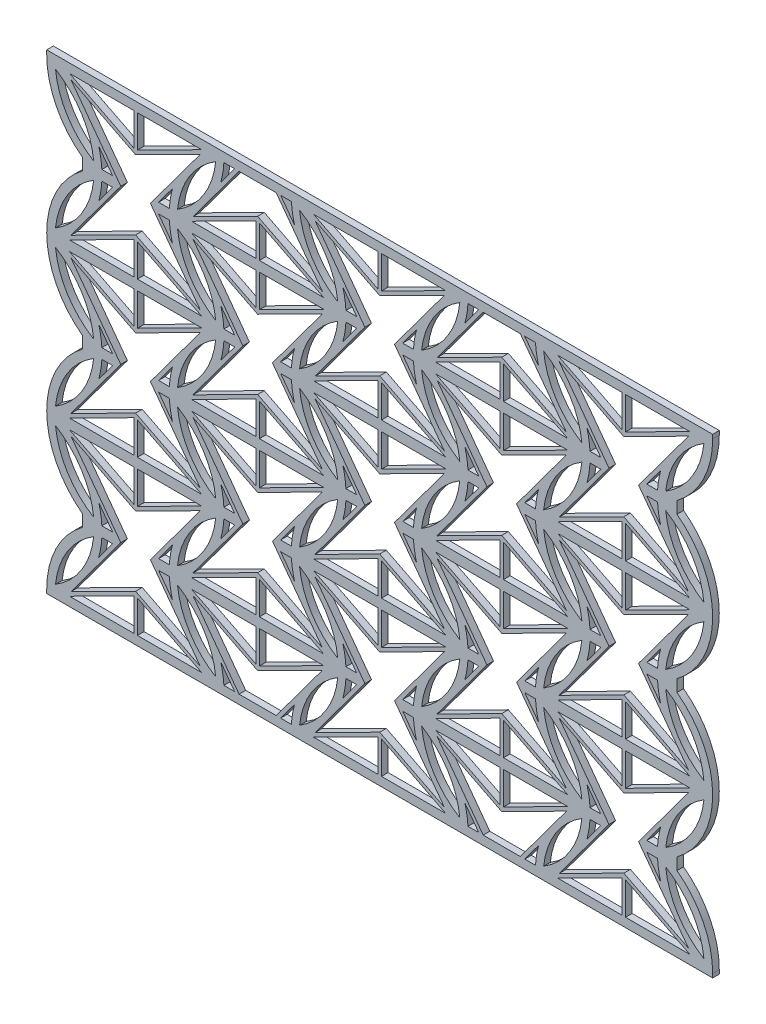
SolidWorks part; units mm, degrees
ref_plane "Front Plane" through (0, 0, 0) normal (0, 0, 1) x (1, 0, 0)
ref_plane "Top Plane" through (0, 0, 0) normal (0, 1, 0) x (1, 0, 0)
ref_plane "Right Plane" through (0, 0, 0) normal (1, 0, 0) x (0, 0, -1)
sketch "Sketch1" plane through (0, 0, 0) normal (0, 0, 1) x (1, 0, 0)
  line L1 (3.3776, -1.5756) -> (5.3265, -1.5756)
  line L3 (-16.8885, 13.319) -> (-16.8885, 14.0355) construction
  line L6 (15.3115, 14.0355) -> (15.3115, 13.319) construction
  line L8 (-4.9547, -1.5756) -> (-6.9036, -1.5756)
  line L9 (-16.8885, -14.6332) -> (-16.8885, -15.3497)
  line L10 (-4.9547, 0.2614) -> (-7.4694, 3.6583)
  line L11 (-16.8885, -15.3497) -> (15.3115, -15.3497)
  line L13 (-10.427, 0.423) -> (-10.427, -1.7372)
  line L16 (-16.8885, 13.319) -> (15.3115, 13.319) construction
  line L17 (11.1755, 12.4005) -> (-0.4651, 12.4005)
  line L21 (3.3776, 0.2614) -> (5.8924, 3.6583)
  line L23 (-1.112, 6.5213) -> (-12.7526, 12.4005)
  line L24 (3.3776, -1.5756) -> (5.8924, -4.9725)
  line L25 (3.3776, 0.2614) -> (5.3265, 0.2614)
  line L27 (-4.9547, -1.5756) -> (-7.4694, -4.9725)
  line L28 (-4.9547, 0.2614) -> (-6.9036, 0.2614)
  line L30 (-16.8885, 14.0355) -> (15.3115, 14.0355) construction
  line L31 (-1.112, 12.4005) -> (-12.7526, 12.4005)
  line L33 (15.3115, -15.3497) -> (15.3115, -14.6332) construction
  line L34 (-16.8885, -14.6332) -> (15.3115, -14.6332) construction
  line L36 (8.85, 0.423) -> (8.85, -1.7372) construction
  line L40 (-0.4651, 6.5213) -> (11.1755, 12.4005)
  line L41 (-0.7885, 4.2888) -> (-0.7885, -49995.7112) construction
  line L42 (-1.9767, -0.6571) -> (49998.0233, -0.6571) construction
  line L43 (-1.112, 12.4005) -> (-1.112, 6.5213)
  line L44 (-0.4651, 12.4005) -> (-0.4651, 6.5213)
  line L45 (-0.7885, -6.9474) -> (10.932, -12.867)
  line L46 (10.932, -12.867) -> (1.8927, -0.6571)
  line L47 (10.932, 11.5528) -> (1.8927, -0.6571)
  line L48 (-0.7885, 5.6332) -> (10.932, 11.5528)
  line L49 (-0.7885, 5.6332) -> (-12.509, 11.5528)
  line L50 (-12.509, 11.5528) -> (-3.4698, -0.6571)
  line L51 (-12.509, -12.867) -> (-3.4698, -0.6571)
  line L52 (-0.7885, -6.9474) -> (-12.509, -12.867)
  line L53 (-0.4651, -7.8355) -> (11.1755, -13.7147)
  line L54 (-0.4651, -13.7147) -> (-0.4651, -7.8355)
  line L55 (11.1755, -13.7147) -> (-0.4651, -13.7147)
  line L56 (-1.112, -13.7147) -> (-1.112, -7.8355)
  line L57 (-1.112, -7.8355) -> (-12.7526, -13.7147)
  line L58 (-1.112, -13.7147) -> (-12.7526, -13.7147)
  line L59 (25.4851, 14.2376) -> (27.434, 14.2376)
  line L60 (33.283, 0.2614) -> (21.6424, 0.2614)
  line L61 (37.4189, -1.3736) -> (37.4189, -0.6571) construction
  line L62 (21.3189, 19.6093) -> (9.5984, 25.5289)
  line L63 (5.2189, 27.2952) -> (37.4189, 27.2952) construction
  line L64 (9.5984, 1.1091) -> (18.6377, 13.319)
  line L65 (17.1528, 14.2376) -> (15.2039, 14.2376)
  line L66 (21.6424, 6.1407) -> (33.283, 0.2614)
  line L67 (20.9955, 0.2614) -> (9.3549, 0.2614)
  line L68 (17.1528, 12.4005) -> (15.2039, 12.4005)
  line L69 (17.1528, 14.2376) -> (14.638, 17.6344)
  line L70 (25.4851, 14.2376) -> (27.9998, 17.6344)
  line L71 (9.5984, 25.5289) -> (18.6377, 13.319)
  line L72 (11.6804, 14.3991) -> (11.6804, 12.239) construction
  line L73 (20.9955, 6.1407) -> (9.3549, 0.2614)
  line L74 (5.2189, 28.0116) -> (37.4189, 28.0116) construction
  line L75 (33.0394, 1.1091) -> (24.0002, 13.319)
  line L76 (25.4851, 12.4005) -> (27.434, 12.4005)
  line L77 (21.3189, 7.0287) -> (9.5984, 1.1091)
  line L78 (5.2189, 27.2952) -> (5.2189, 28.0116) construction
  line L79 (33.283, 26.3766) -> (21.6424, 26.3766)
  line L80 (21.6424, 20.4974) -> (33.283, 26.3766)
  line L81 (30.9574, 14.3991) -> (30.9574, 12.239) construction
  line L82 (20.9955, 20.4974) -> (9.3549, 26.3766)
  line L83 (20.9955, 26.3766) -> (20.9955, 20.4974)
  line L84 (21.3189, 7.0287) -> (33.0394, 1.1091)
  line L85 (25.4851, 12.4005) -> (27.9998, 9.0036)
  line L86 (33.0394, 25.5289) -> (24.0002, 13.319)
  line L87 (5.2189, -0.6571) -> (5.2189, -1.3736) construction
  line L88 (17.1528, 12.4005) -> (14.638, 9.0036)
  line L89 (20.9955, 0.2614) -> (20.9955, 6.1407)
  line L90 (5.2189, -1.3736) -> (37.4189, -1.3736) construction
  line L91 (20.9955, 26.3766) -> (9.3549, 26.3766)
  line L92 (21.6424, 0.2614) -> (21.6424, 6.1407)
  line L93 (37.4189, 28.0116) -> (37.4189, 27.2952) construction
  line L94 (21.3189, 19.6093) -> (33.0394, 25.5289)
  line L95 (5.2189, -0.6571) -> (37.4189, -0.6571) construction
  line L96 (21.6424, 26.3766) -> (21.6424, 20.4974)
  line L97 (47.5925, 28.2137) -> (49.5414, 28.2137)
  line L98 (55.3904, 14.2376) -> (43.7498, 14.2376)
  line L99 (59.5264, 12.6026) -> (59.5264, 13.319) construction
  line L100 (43.4264, 33.5855) -> (31.7059, 39.5051)
  line L101 (27.3264, 41.2713) -> (59.5264, 41.2713) construction
  line L102 (31.7059, 15.0853) -> (40.7451, 27.2952)
  line L103 (39.2602, 28.2137) -> (37.3113, 28.2137)
  line L104 (43.7498, 20.1168) -> (55.3904, 14.2376)
  line L105 (43.1029, 14.2376) -> (31.4623, 14.2376)
  line L106 (39.2602, 26.3766) -> (37.3113, 26.3766)
  line L107 (39.2602, 28.2137) -> (36.7455, 31.6106)
  line L108 (47.5925, 28.2137) -> (50.1073, 31.6106)
  line L109 (31.7059, 39.5051) -> (40.7451, 27.2952)
  line L110 (33.7879, 28.3752) -> (33.7879, 26.2151) construction
  line L111 (43.1029, 20.1168) -> (31.4623, 14.2376)
  line L112 (27.3264, 41.9878) -> (59.5264, 41.9878) construction
  line L113 (55.1469, 15.0853) -> (46.1076, 27.2952)
  line L114 (47.5925, 26.3766) -> (49.5414, 26.3766)
  line L115 (43.4264, 21.0049) -> (31.7059, 15.0853)
  line L116 (27.3264, 41.2713) -> (27.3264, 41.9878) construction
  line L117 (55.3904, 40.3528) -> (43.7498, 40.3528)
  line L118 (43.7498, 34.4735) -> (55.3904, 40.3528)
  line L119 (53.0649, 28.3752) -> (53.0649, 26.2151) construction
  line L120 (43.1029, 34.4735) -> (31.4623, 40.3528)
  line L121 (43.1029, 40.3528) -> (43.1029, 34.4735)
  line L122 (43.4264, 21.0049) -> (55.1469, 15.0853)
  line L123 (47.5925, 26.3766) -> (50.1073, 22.9798)
  line L124 (55.1469, 39.5051) -> (46.1076, 27.2952)
  line L125 (27.3264, 13.319) -> (27.3264, 12.6026) construction
  line L126 (39.2602, 26.3766) -> (36.7455, 22.9798)
  line L127 (43.1029, 14.2376) -> (43.1029, 20.1168)
  line L128 (27.3264, 12.6026) -> (59.5264, 12.6026) construction
  line L129 (43.1029, 40.3528) -> (31.4623, 40.3528)
  line L130 (43.7498, 14.2376) -> (43.7498, 20.1168)
  line L131 (59.5264, 41.9878) -> (59.5264, 41.2713) construction
  line L132 (43.4264, 33.5855) -> (55.1469, 39.5051)
  line L133 (27.3264, 13.319) -> (59.5264, 13.319) construction
  line L134 (43.7498, 40.3528) -> (43.7498, 34.4735)
  line L135 (69.7, 42.1898) -> (71.6489, 42.1898)
  line L136 (77.4979, 28.2137) -> (65.8573, 28.2137)
  line L137 (81.6338, 26.5787) -> (81.6338, 27.2952) construction
  line L138 (65.5338, 47.5616) -> (53.8133, 53.4812)
  line L139 (49.4338, 55.2475) -> (81.6338, 55.2475) construction
  line L140 (53.8133, 29.0614) -> (62.8526, 41.2713)
  line L141 (61.3677, 42.1898) -> (59.4188, 42.1898)
  line L142 (65.8573, 34.093) -> (77.4979, 28.2137)
  line L143 (65.2104, 28.2137) -> (53.5698, 28.2137)
  line L144 (61.3677, 40.3528) -> (59.4188, 40.3528)
  line L145 (61.3677, 42.1898) -> (58.8529, 45.5867)
  line L146 (69.7, 42.1898) -> (72.2147, 45.5867)
  line L147 (53.8133, 53.4812) -> (62.8526, 41.2713)
  line L148 (55.8953, 42.3514) -> (55.8953, 40.1913) construction
  line L149 (65.2104, 34.093) -> (53.5698, 28.2137)
  line L150 (49.4338, 55.9639) -> (81.6338, 55.9639) construction
  line L151 (77.2543, 29.0614) -> (68.2151, 41.2713)
  line L152 (69.7, 40.3528) -> (71.6489, 40.3528)
  line L153 (65.5338, 34.981) -> (53.8133, 29.0614)
  line L154 (49.4338, 55.2475) -> (49.4338, 55.9639) construction
  line L155 (77.4979, 54.3289) -> (65.8573, 54.3289)
  line L156 (65.8573, 48.4497) -> (77.4979, 54.3289)
  line L157 (75.1723, 42.3514) -> (75.1723, 40.1913) construction
  line L158 (65.2104, 48.4497) -> (53.5698, 54.3289)
  line L159 (65.2104, 54.3289) -> (65.2104, 48.4497)
  line L160 (65.5338, 34.981) -> (77.2543, 29.0614)
  line L161 (69.7, 40.3528) -> (72.2147, 36.9559)
  line L162 (77.2543, 53.4812) -> (68.2151, 41.2713)
  line L163 (49.4338, 27.2952) -> (49.4338, 26.5787) construction
  line L164 (61.3677, 40.3528) -> (58.8529, 36.9559)
  line L165 (65.2104, 28.2137) -> (65.2104, 34.093)
  line L166 (49.4338, 26.5787) -> (81.6338, 26.5787) construction
  line L167 (65.2104, 54.3289) -> (53.5698, 54.3289)
  line L168 (65.8573, 28.2137) -> (65.8573, 34.093)
  line L169 (81.6338, 55.9639) -> (81.6338, 55.2475) construction
  line L170 (65.5338, 47.5616) -> (77.2543, 53.4812)
  line L171 (49.4338, 27.2952) -> (81.6338, 27.2952) construction
  line L172 (65.8573, 54.3289) -> (65.8573, 48.4497)
  line L173 (91.8074, 56.166) -> (93.7563, 56.166)
  line L174 (99.6053, 42.1898) -> (87.9647, 42.1898)
  line L175 (103.7413, 40.5549) -> (103.7413, 41.2713) construction
  line L176 (87.6413, 61.5378) -> (75.9208, 67.4574)
  line L177 (71.5413, 69.2236) -> (103.7413, 69.2236) construction
  line L178 (75.9208, 43.0376) -> (84.96, 55.2475)
  line L179 (83.4751, 56.166) -> (81.5262, 56.166)
  line L180 (87.9647, 48.0691) -> (99.6053, 42.1898)
  line L181 (87.3178, 42.1898) -> (75.6772, 42.1898)
  line L182 (83.4751, 54.3289) -> (81.5262, 54.3289)
  line L183 (83.4751, 56.166) -> (80.9604, 59.5629)
  line L184 (91.8074, 56.166) -> (94.3222, 59.5629)
  line L185 (75.9208, 67.4574) -> (84.96, 55.2475)
  line L186 (78.0027, 56.3275) -> (78.0027, 54.1674) construction
  line L187 (87.3178, 48.0691) -> (75.6772, 42.1898)
  line L188 (71.5413, 69.94) -> (103.7413, 69.94)
  line L189 (99.3618, 43.0376) -> (90.3225, 55.2475)
  line L190 (91.8074, 54.3289) -> (93.7563, 54.3289)
  line L191 (87.6413, 48.9572) -> (75.9208, 43.0376)
  line L192 (71.5413, 69.2236) -> (71.5413, 69.94) construction
  line L193 (99.6053, 68.3051) -> (87.9647, 68.3051)
  line L194 (87.9647, 62.4258) -> (99.6053, 68.3051)
  line L195 (97.2798, 56.3275) -> (97.2798, 54.1674)
  line L196 (87.3178, 62.4258) -> (75.6772, 68.3051)
  line L197 (87.3178, 68.3051) -> (87.3178, 62.4258)
  line L198 (87.6413, 48.9572) -> (99.3618, 43.0376)
  line L199 (91.8074, 54.3289) -> (94.3222, 50.932)
  line L200 (99.3618, 67.4574) -> (90.3225, 55.2475)
  line L201 (71.5413, 41.2713) -> (71.5413, 40.5549) construction
  line L202 (83.4751, 54.3289) -> (80.9604, 50.932)
  line L203 (87.3178, 42.1898) -> (87.3178, 48.0691)
  line L204 (71.5413, 40.5549) -> (103.7413, 40.5549) construction
  line L205 (87.3178, 68.3051) -> (75.6772, 68.3051)
  line L206 (87.9647, 42.1898) -> (87.9647, 48.0691)
  line L207 (103.7413, 69.94) -> (103.7413, 69.2236)
  line L208 (87.6413, 61.5378) -> (99.3618, 67.4574)
  line L209 (71.5413, 41.2713) -> (103.7413, 41.2713) construction
  line L210 (87.9647, 68.3051) -> (87.9647, 62.4258)
  line L211 (20.9955, 48.4497) -> (9.3549, 54.3289)
  line L212 (20.9955, 54.3289) -> (20.9955, 48.4497)
  line L213 (30.9574, 42.3514) -> (30.9574, 40.1913) construction
  line L214 (17.1528, 40.3528) -> (15.2039, 40.3528)
  line L215 (21.6424, 54.3289) -> (21.6424, 48.4497)
  line L216 (5.2189, 27.2952) -> (5.2189, 26.5787) construction
  line L217 (21.6424, 48.4497) -> (33.283, 54.3289)
  line L218 (5.2189, 26.5787) -> (37.4189, 26.5787) construction
  line L219 (17.1528, 40.3528) -> (14.638, 36.9559)
  line L220 (33.283, 28.2137) -> (21.6424, 28.2137)
  line L221 (21.3189, 34.981) -> (33.0394, 29.0614)
  line L222 (9.5984, 53.4812) -> (18.6377, 41.2713)
  line L223 (33.283, 54.3289) -> (21.6424, 54.3289)
  line L224 (21.6424, 28.2137) -> (21.6424, 34.093)
  line L225 (21.3189, 47.5616) -> (33.0394, 53.4812)
  line L226 (21.6424, 34.093) -> (33.283, 28.2137)
  line L227 (5.2189, 55.2475) -> (5.2189, 55.9639) construction
  line L228 (37.4189, 26.5787) -> (37.4189, 27.2952) construction
  line L229 (17.1528, 42.1898) -> (15.2039, 42.1898)
  line L230 (5.2189, 55.2475) -> (37.4189, 55.2475) construction
  line L231 (25.4851, 40.3528) -> (27.434, 40.3528)
  line L232 (33.0394, 29.0614) -> (24.0002, 41.2713)
  line L233 (17.1528, 42.1898) -> (14.638, 45.5867)
  line L234 (20.9955, 34.093) -> (9.3549, 28.2137)
  line L235 (5.2189, 55.9639) -> (37.4189, 55.9639) construction
  line L236 (25.4851, 42.1898) -> (27.434, 42.1898)
  line L237 (20.9955, 28.2137) -> (9.3549, 28.2137)
  line L238 (21.3189, 47.5616) -> (9.5984, 53.4812)
  line L239 (25.4851, 42.1898) -> (27.9998, 45.5867)
  line L240 (9.5984, 29.0614) -> (18.6377, 41.2713)
  line L241 (33.0394, 53.4812) -> (24.0002, 41.2713)
  line L242 (20.9955, 28.2137) -> (20.9955, 34.093)
  line L243 (37.4189, 55.9639) -> (37.4189, 55.2475) construction
  line L244 (20.9955, 54.3289) -> (9.3549, 54.3289)
  line L245 (5.2189, 27.2952) -> (37.4189, 27.2952) construction
  line L246 (25.4851, 40.3528) -> (27.9998, 36.9559)
  line L247 (21.3189, 34.981) -> (9.5984, 29.0614)
  line L248 (11.6804, 42.3514) -> (11.6804, 40.1913) construction
  line L249 (43.1029, 62.4258) -> (31.4623, 68.3051)
  line L250 (43.1029, 68.3051) -> (43.1029, 62.4258)
  line L251 (53.0649, 56.3275) -> (53.0649, 54.1674) construction
  line L252 (39.2602, 54.3289) -> (37.3113, 54.3289)
  line L253 (43.7498, 68.3051) -> (43.7498, 62.4258)
  line L254 (27.3264, 41.2713) -> (27.3264, 40.5549) construction
  line L255 (43.7498, 62.4258) -> (55.3904, 68.3051)
  line L256 (27.3264, 40.5549) -> (59.5264, 40.5549) construction
  line L257 (39.2602, 54.3289) -> (36.7455, 50.932)
  line L258 (55.3904, 42.1898) -> (43.7498, 42.1898)
  line L259 (43.4264, 48.9572) -> (55.1469, 43.0376)
  line L260 (31.7059, 67.4574) -> (40.7451, 55.2475)
  line L261 (55.3904, 68.3051) -> (43.7498, 68.3051)
  line L262 (43.7498, 42.1898) -> (43.7498, 48.0691)
  line L263 (43.4264, 61.5378) -> (55.1469, 67.4574)
  line L264 (43.7498, 48.0691) -> (55.3904, 42.1898)
  line L265 (27.3264, 69.2236) -> (27.3264, 69.94) construction
  line L266 (59.5264, 40.5549) -> (59.5264, 41.2713) construction
  line L267 (39.2602, 56.166) -> (37.3113, 56.166)
  line L268 (27.3264, 69.2236) -> (59.5264, 69.2236) construction
  line L269 (47.5925, 54.3289) -> (49.5414, 54.3289)
  line L270 (55.1469, 43.0376) -> (46.1076, 55.2475)
  line L271 (39.2602, 56.166) -> (36.7455, 59.5629)
  line L272 (43.1029, 48.0691) -> (31.4623, 42.1898)
  line L273 (27.3264, 69.94) -> (59.5264, 69.94)
  line L274 (47.5925, 56.166) -> (49.5414, 56.166)
  line L275 (43.1029, 42.1898) -> (31.4623, 42.1898)
  line L276 (43.4264, 61.5378) -> (31.7059, 67.4574)
  line L277 (47.5925, 56.166) -> (50.1073, 59.5629)
  line L278 (31.7059, 43.0376) -> (40.7451, 55.2475)
  line L279 (55.1469, 67.4574) -> (46.1076, 55.2475)
  line L280 (43.1029, 42.1898) -> (43.1029, 48.0691)
  line L281 (59.5264, 69.94) -> (59.5264, 69.2236) construction
  line L282 (43.1029, 68.3051) -> (31.4623, 68.3051)
  line L283 (27.3264, 41.2713) -> (59.5264, 41.2713) construction
  line L284 (47.5925, 54.3289) -> (50.1073, 50.932)
  line L285 (43.4264, 48.9572) -> (31.7059, 43.0376)
  line L286 (33.7879, 56.3275) -> (33.7879, 54.1674) construction
  line L287 (65.2104, 76.402) -> (53.5698, 82.2812) construction
  line L288 (65.2104, 82.2812) -> (65.2104, 76.402) construction
  line L289 (75.1723, 70.3037) -> (75.1723, 68.1435) construction
  line L290 (61.3677, 68.3051) -> (59.4188, 68.3051)
  line L291 (65.8573, 82.2812) -> (65.8573, 76.402) construction
  line L292 (49.4338, 55.2475) -> (49.4338, 54.531) construction
  line L293 (65.8573, 76.402) -> (77.4979, 82.2812) construction
  line L294 (49.4338, 54.531) -> (81.6338, 54.531) construction
  line L295 (61.3677, 68.3051) -> (58.8529, 64.9082)
  line L296 (77.4979, 56.166) -> (65.8573, 56.166)
  line L297 (65.5338, 62.9333) -> (77.2543, 57.0137)
  line L299 (77.4979, 82.2812) -> (65.8573, 82.2812) construction
  line L300 (65.8573, 56.166) -> (65.8573, 62.0452)
  line L302 (65.8573, 62.0452) -> (77.4979, 56.166)
  line L303 (49.4338, 83.1997) -> (49.4338, 83.9162) construction
  line L304 (81.6338, 54.531) -> (81.6338, 55.2475) construction
  line L305 (61.3677, 70.1421) -> (59.4188, 70.1421) construction
  line L306 (49.4338, 83.1997) -> (81.6338, 83.1997) construction
  line L307 (69.7, 68.3051) -> (71.6489, 68.3051)
  line L308 (77.2543, 57.0137) -> (68.8951, 68.3051)
  line L309 (61.3677, 70.1421) -> (58.8529, 73.539) construction
  line L310 (65.2104, 62.0452) -> (53.5698, 56.166)
  line L311 (49.4338, 83.9162) -> (81.6338, 83.9162) construction
  line L312 (69.7, 70.1421) -> (71.6489, 70.1421) construction
  line L313 (65.2104, 56.166) -> (53.5698, 56.166)
  line L315 (69.7, 70.1421) -> (72.2147, 73.539) construction
  line L316 (53.8133, 57.0137) -> (62.1725, 68.3051)
  line L318 (65.2104, 56.166) -> (65.2104, 62.0452)
  line L319 (81.6338, 83.9162) -> (81.6338, 83.1997) construction
  line L320 (65.2104, 82.2812) -> (53.5698, 82.2812) construction
  line L321 (49.4338, 55.2475) -> (81.6338, 55.2475) construction
  line L322 (69.7, 68.3051) -> (72.2147, 64.9082)
  line L323 (65.5338, 62.9333) -> (53.8133, 57.0137)
  line L324 (55.8953, 70.3037) -> (55.8953, 68.1435) construction
  line L325 (-1.112, 34.4735) -> (-12.7526, 40.3528)
  line L326 (-1.112, 40.3528) -> (-1.112, 34.4735)
  line L327 (8.85, 28.3752) -> (8.85, 26.2151) construction
  line L328 (-4.9547, 26.3766) -> (-6.9036, 26.3766)
  line L329 (-0.4651, 40.3528) -> (-0.4651, 34.4735)
  line L330 (-16.8885, 13.319) -> (-16.8885, 12.6026) construction
  line L331 (-0.4651, 34.4735) -> (11.1755, 40.3528)
  line L332 (-16.8885, 12.6026) -> (15.3115, 12.6026) construction
  line L333 (-4.9547, 26.3766) -> (-7.4694, 22.9798)
  line L334 (11.1755, 14.2376) -> (-0.4651, 14.2376)
  line L335 (-0.7885, 21.0049) -> (10.932, 15.0853)
  line L336 (-12.509, 39.5051) -> (-3.4698, 27.2952)
  line L337 (11.1755, 40.3528) -> (-0.4651, 40.3528)
  line L338 (-0.4651, 14.2376) -> (-0.4651, 20.1168)
  line L339 (-0.7885, 33.5855) -> (10.932, 39.5051)
  line L340 (-0.4651, 20.1168) -> (11.1755, 14.2376)
  line L341 (-16.8885, 41.2713) -> (-16.8885, 41.9878) construction
  line L342 (15.3115, 12.6026) -> (15.3115, 13.319) construction
  line L343 (-4.9547, 28.2137) -> (-6.9036, 28.2137)
  line L344 (-16.8885, 41.2713) -> (15.3115, 41.2713) construction
  line L345 (3.3776, 26.3766) -> (5.3265, 26.3766)
  line L346 (10.932, 15.0853) -> (1.8927, 27.2952)
  line L347 (-4.9547, 28.2137) -> (-7.4694, 31.6106)
  line L348 (-1.112, 20.1168) -> (-12.7526, 14.2376)
  line L349 (-16.8885, 41.9878) -> (15.3115, 41.9878) construction
  line L350 (3.3776, 28.2137) -> (5.3265, 28.2137)
  line L351 (-1.112, 14.2376) -> (-12.7526, 14.2376)
  line L352 (-0.7885, 33.5855) -> (-12.509, 39.5051)
  line L353 (3.3776, 28.2137) -> (5.8924, 31.6106)
  line L354 (-12.509, 15.0853) -> (-3.4698, 27.2952)
  line L355 (10.932, 39.5051) -> (1.8927, 27.2952)
  line L356 (-1.112, 14.2376) -> (-1.112, 20.1168)
  line L357 (15.3115, 41.9878) -> (15.3115, 41.2713) construction
  line L358 (-1.112, 40.3528) -> (-12.7526, 40.3528)
  line L359 (-16.8885, 13.319) -> (15.3115, 13.319) construction
  line L360 (3.3776, 26.3766) -> (5.8924, 22.9798)
  line L361 (-0.7885, 21.0049) -> (-12.509, 15.0853)
  line L362 (-10.427, 28.3752) -> (-10.427, 26.2151)
  line L363 (-1.112, 62.4258) -> (-12.7526, 68.3051)
  line L364 (-1.112, 68.3051) -> (-1.112, 62.4258)
  line L365 (8.85, 56.3275) -> (8.85, 54.1674) construction
  line L366 (-4.9547, 54.3289) -> (-6.9036, 54.3289)
  line L367 (-0.4651, 68.3051) -> (-0.4651, 62.4258)
  line L368 (-16.8885, 41.2713) -> (-16.8885, 40.5549) construction
  line L369 (-0.4651, 62.4258) -> (11.1755, 68.3051)
  line L370 (-16.8885, 40.5549) -> (15.3115, 40.5549) construction
  line L371 (-4.9547, 54.3289) -> (-7.4694, 50.932)
  line L372 (11.1755, 42.1898) -> (-0.4651, 42.1898)
  line L373 (-0.7885, 48.9572) -> (10.932, 43.0376)
  line L374 (-12.509, 67.4574) -> (-3.4698, 55.2475)
  line L375 (11.1755, 68.3051) -> (-0.4651, 68.3051)
  line L376 (-0.4651, 42.1898) -> (-0.4651, 48.0691)
  line L377 (-0.7885, 61.5378) -> (10.932, 67.4574)
  line L378 (-0.4651, 48.0691) -> (11.1755, 42.1898)
  line L379 (-16.8885, 69.2236) -> (-16.8885, 69.94)
  line L380 (15.3115, 40.5549) -> (15.3115, 41.2713) construction
  line L381 (-4.9547, 56.166) -> (-6.9036, 56.166)
  line L382 (-16.8885, 69.2236) -> (15.3115, 69.2236) construction
  line L383 (3.3776, 54.3289) -> (5.3265, 54.3289)
  line L384 (10.932, 43.0376) -> (1.8927, 55.2475)
  line L385 (-4.9547, 56.166) -> (-7.4694, 59.5629)
  line L386 (-1.112, 48.0691) -> (-12.7526, 42.1898)
  line L387 (-16.8885, 69.94) -> (15.3115, 69.94)
  line L388 (3.3776, 56.166) -> (5.3265, 56.166)
  line L389 (-1.112, 42.1898) -> (-12.7526, 42.1898)
  line L390 (-0.7885, 61.5378) -> (-12.509, 67.4574)
  line L391 (3.3776, 56.166) -> (5.8924, 59.5629)
  line L392 (-12.509, 43.0376) -> (-3.4698, 55.2475)
  line L393 (10.932, 67.4574) -> (1.8927, 55.2475)
  line L394 (-1.112, 42.1898) -> (-1.112, 48.0691)
  line L395 (15.3115, 69.94) -> (15.3115, 69.2236) construction
  line L396 (-1.112, 68.3051) -> (-12.7526, 68.3051)
  line L397 (-16.8885, 41.2713) -> (15.3115, 41.2713) construction
  line L398 (3.3776, 54.3289) -> (5.8924, 50.932)
  line L399 (-0.7885, 48.9572) -> (-12.509, 43.0376)
  line L400 (-10.427, 56.3275) -> (-10.427, 54.1674)
  line L401 (20.9955, 76.402) -> (9.3549, 82.2812) construction
  line L402 (20.9955, 82.2812) -> (20.9955, 76.402) construction
  line L403 (30.9574, 70.3037) -> (30.9574, 68.1435) construction
  line L404 (17.1528, 68.3051) -> (15.2039, 68.3051)
  line L405 (21.6424, 82.2812) -> (21.6424, 76.402) construction
  line L406 (5.2189, 55.2475) -> (5.2189, 54.531) construction
  line L407 (21.6424, 76.402) -> (33.283, 82.2812) construction
  line L408 (5.2189, 54.531) -> (37.4189, 54.531) construction
  line L409 (17.1528, 68.3051) -> (14.638, 64.9082)
  line L410 (33.283, 56.166) -> (21.6424, 56.166)
  line L411 (21.3189, 62.9333) -> (33.0394, 57.0137)
  line L413 (33.283, 82.2812) -> (21.6424, 82.2812) construction
  line L414 (21.6424, 56.166) -> (21.6424, 62.0452)
  line L416 (21.6424, 62.0452) -> (33.283, 56.166)
  line L417 (5.2189, 83.1997) -> (5.2189, 83.9162) construction
  line L418 (37.4189, 54.531) -> (37.4189, 55.2475) construction
  line L419 (17.1528, 70.1421) -> (15.2039, 70.1421) construction
  line L420 (5.2189, 83.1997) -> (37.4189, 83.1997) construction
  line L421 (25.4851, 68.3051) -> (27.434, 68.3051)
  line L422 (33.0394, 57.0137) -> (24.6802, 68.3051)
  line L423 (17.1528, 70.1421) -> (14.638, 73.539) construction
  line L424 (20.9955, 62.0452) -> (9.3549, 56.166)
  line L425 (5.2189, 83.9162) -> (37.4189, 83.9162) construction
  line L426 (25.4851, 70.1421) -> (27.434, 70.1421) construction
  line L427 (20.9955, 56.166) -> (9.3549, 56.166)
  line L429 (25.4851, 70.1421) -> (27.9998, 73.539) construction
  line L430 (9.5984, 57.0137) -> (17.9577, 68.3051)
  line L432 (20.9955, 56.166) -> (20.9955, 62.0452)
  line L433 (37.4189, 83.9162) -> (37.4189, 83.1997) construction
  line L434 (20.9955, 82.2812) -> (9.3549, 82.2812) construction
  line L435 (5.2189, 55.2475) -> (37.4189, 55.2475) construction
  line L436 (25.4851, 68.3051) -> (27.9998, 64.9082)
  line L437 (21.3189, 62.9333) -> (9.5984, 57.0137)
  line L438 (11.6804, 70.3037) -> (11.6804, 68.1435) construction
  line L439 (39.2602, 0.2614) -> (36.7455, 3.6583)
  line L440 (43.1029, -13.7147) -> (43.1029, -7.8355)
  line L441 (27.3264, 14.0355) -> (59.5264, 14.0355) construction
  line L442 (55.3904, 12.4005) -> (43.7498, 12.4005)
  line L443 (43.7498, -13.7147) -> (43.7498, -7.8355)
  line L444 (33.7879, 0.423) -> (33.7879, -1.7372) construction
  line L445 (39.2602, -1.5756) -> (36.7455, -4.9725)
  line L446 (43.1029, -13.7147) -> (31.4623, -13.7147)
  line L447 (53.0649, 0.423) -> (53.0649, -1.7372) construction
  line L448 (47.5925, 0.2614) -> (50.1073, 3.6583)
  line L449 (43.1029, 12.4005) -> (43.1029, 6.5213)
  line L450 (27.3264, -14.6332) -> (59.5264, -14.6332) construction
  line L451 (55.1469, -12.867) -> (46.1076, -0.6571)
  line L452 (43.1029, 12.4005) -> (31.4623, 12.4005)
  line L453 (43.4264, 5.6332) -> (31.7059, 11.5528)
  line L454 (43.4264, -6.9474) -> (55.1469, -12.867)
  line L455 (43.4264, -6.9474) -> (31.7059, -12.867)
  line L456 (59.5264, 14.0355) -> (59.5264, 13.319) construction
  line L457 (47.5925, -1.5756) -> (49.5414, -1.5756)
  line L458 (55.3904, -13.7147) -> (43.7498, -13.7147)
  line L459 (27.3264, -15.3497) -> (59.5264, -15.3497)
  line L460 (31.7059, 11.5528) -> (40.7451, -0.6571)
  line L461 (31.7059, -12.867) -> (40.7451, -0.6571)
  line L462 (27.3264, 13.319) -> (59.5264, 13.319) construction
  line L463 (47.5925, 0.2614) -> (49.5414, 0.2614)
  line L464 (43.1029, -7.8355) -> (31.4623, -13.7147)
  line L465 (27.3264, -14.6332) -> (27.3264, -15.3497) construction
  line L466 (59.5264, -15.3497) -> (59.5264, -14.6332) construction
  line L467 (43.7498, 6.5213) -> (55.3904, 12.4005)
  line L468 (43.1029, 6.5213) -> (31.4623, 12.4005)
  line L469 (27.3264, 13.319) -> (27.3264, 14.0355) construction
  line L470 (43.7498, 12.4005) -> (43.7498, 6.5213)
  line L471 (39.2602, -1.5756) -> (37.3113, -1.5756)
  line L472 (43.4264, 5.6332) -> (55.1469, 11.5528)
  line L473 (39.2602, 0.2614) -> (37.3113, 0.2614)
  line L474 (55.1469, 11.5528) -> (46.1076, -0.6571)
  line L475 (47.5925, -1.5756) -> (50.1073, -4.9725)
  line L476 (43.7498, -7.8355) -> (55.3904, -13.7147)
  line L477 (61.3677, 14.2376) -> (58.8529, 17.6344)
  line L478 (65.2104, 0.2614) -> (65.2104, 6.1407)
  line L479 (49.4338, 28.0116) -> (81.6338, 28.0116) construction
  line L480 (77.4979, 26.3766) -> (65.8573, 26.3766)
  line L481 (65.8573, 0.2614) -> (65.8573, 6.1407)
  line L482 (55.8953, 14.3991) -> (55.8953, 12.239) construction
  line L483 (61.3677, 12.4005) -> (58.8529, 9.0036)
  line L484 (65.2104, 0.2614) -> (53.5698, 0.2614)
  line L485 (75.1723, 14.3991) -> (75.1723, 12.239) construction
  line L486 (69.7, 14.2376) -> (72.2147, 17.6344)
  line L487 (65.2104, 26.3766) -> (65.2104, 20.4974)
  line L488 (49.4338, -0.6571) -> (81.6338, -0.6571) construction
  line L489 (77.2543, 1.1091) -> (68.2151, 13.319)
  line L490 (65.2104, 26.3766) -> (53.5698, 26.3766)
  line L491 (65.5338, 19.6093) -> (53.8133, 25.5289)
  line L492 (65.5338, 7.0287) -> (77.2543, 1.1091)
  line L493 (65.5338, 7.0287) -> (53.8133, 1.1091)
  line L494 (81.6338, 28.0116) -> (81.6338, 27.2952) construction
  line L495 (69.7, 12.4005) -> (71.6489, 12.4005)
  line L496 (77.4979, 0.2614) -> (65.8573, 0.2614)
  line L497 (49.4338, -1.3736) -> (81.6338, -1.3736) construction
  line L498 (53.8133, 25.5289) -> (62.8526, 13.319)
  line L499 (53.8133, 1.1091) -> (62.8526, 13.319)
  line L500 (49.4338, 27.2952) -> (81.6338, 27.2952) construction
  line L501 (69.7, 14.2376) -> (71.6489, 14.2376)
  line L502 (65.2104, 6.1407) -> (53.5698, 0.2614)
  line L503 (49.4338, -0.6571) -> (49.4338, -1.3736) construction
  line L504 (81.6338, -1.3736) -> (81.6338, -0.6571) construction
  line L505 (65.8573, 20.4974) -> (77.4979, 26.3766)
  line L506 (65.2104, 20.4974) -> (53.5698, 26.3766)
  line L507 (49.4338, 27.2952) -> (49.4338, 28.0116) construction
  line L508 (65.8573, 26.3766) -> (65.8573, 20.4974)
  line L509 (61.3677, 12.4005) -> (59.4188, 12.4005)
  line L510 (65.5338, 19.6093) -> (77.2543, 25.5289)
  line L511 (61.3677, 14.2376) -> (59.4188, 14.2376)
  line L512 (77.2543, 25.5289) -> (68.2151, 13.319)
  line L513 (69.7, 12.4005) -> (72.2147, 9.0036)
  line L514 (65.8573, 6.1407) -> (77.4979, 0.2614)
  line L515 (83.4751, 28.2137) -> (80.9604, 31.6106)
  line L516 (87.3178, 14.2376) -> (87.3178, 20.1168)
  line L517 (71.5413, 41.9878) -> (103.7413, 41.9878) construction
  line L518 (99.6053, 40.3528) -> (87.9647, 40.3528)
  line L519 (87.9647, 14.2376) -> (87.9647, 20.1168)
  line L520 (78.0027, 28.3752) -> (78.0027, 26.2151) construction
  line L521 (83.4751, 26.3766) -> (80.9604, 22.9798)
  line L522 (87.3178, 14.2376) -> (75.6772, 14.2376)
  line L523 (97.2798, 28.3752) -> (97.2798, 26.2151)
  line L524 (91.8074, 28.2137) -> (94.3222, 31.6106)
  line L525 (87.3178, 40.3528) -> (87.3178, 34.4735)
  line L526 (71.5413, 13.319) -> (103.7413, 13.319) construction
  line L527 (99.3618, 15.0853) -> (90.3225, 27.2952)
  line L528 (87.3178, 40.3528) -> (75.6772, 40.3528)
  line L529 (87.6413, 33.5855) -> (75.9208, 39.5051)
  line L530 (87.6413, 21.0049) -> (99.3618, 15.0853)
  line L531 (87.6413, 21.0049) -> (75.9208, 15.0853)
  line L532 (103.7413, 41.9878) -> (103.7413, 41.2713) construction
  line L533 (91.8074, 26.3766) -> (93.7563, 26.3766)
  line L534 (99.6053, 14.2376) -> (87.9647, 14.2376)
  line L535 (71.5413, 12.6026) -> (103.7413, 12.6026) construction
  line L536 (75.9208, 39.5051) -> (84.96, 27.2952)
  line L537 (75.9208, 15.0853) -> (84.96, 27.2952)
  line L538 (71.5413, 41.2713) -> (103.7413, 41.2713) construction
  line L539 (91.8074, 28.2137) -> (93.7563, 28.2137)
  line L540 (87.3178, 20.1168) -> (75.6772, 14.2376)
  line L541 (71.5413, 13.319) -> (71.5413, 12.6026) construction
  line L542 (103.7413, 12.6026) -> (103.7413, 13.319) construction
  line L543 (87.9647, 34.4735) -> (99.6053, 40.3528)
  line L544 (87.3178, 34.4735) -> (75.6772, 40.3528)
  line L545 (71.5413, 41.2713) -> (71.5413, 41.9878) construction
  line L546 (87.9647, 40.3528) -> (87.9647, 34.4735)
  line L547 (83.4751, 26.3766) -> (81.5262, 26.3766)
  line L548 (87.6413, 33.5855) -> (99.3618, 39.5051)
  line L549 (83.4751, 28.2137) -> (81.5262, 28.2137)
  line L550 (99.3618, 39.5051) -> (90.3225, 27.2952)
  line L551 (91.8074, 26.3766) -> (94.3222, 22.9798)
  line L552 (87.9647, 20.1168) -> (99.6053, 14.2376)
  line L553 (83.4751, 0.2614) -> (80.9604, 3.6583)
  line L554 (87.3178, -13.7147) -> (87.3178, -7.8355)
  line L555 (71.5413, 14.0355) -> (103.7413, 14.0355) construction
  line L556 (99.6053, 12.4005) -> (87.9647, 12.4005)
  line L557 (87.9647, -13.7147) -> (87.9647, -7.8355)
  line L558 (78.0027, 0.423) -> (78.0027, -1.7372) construction
  line L559 (83.4751, -1.5756) -> (80.9604, -4.9725)
  line L560 (87.3178, -13.7147) -> (75.6772, -13.7147)
  line L561 (97.2798, 0.423) -> (97.2798, -1.7372)
  line L562 (91.8074, 0.2614) -> (94.3222, 3.6583)
  line L563 (87.3178, 12.4005) -> (87.3178, 6.5213)
  line L564 (71.5413, -14.6332) -> (103.7413, -14.6332) construction
  line L565 (99.3618, -12.867) -> (90.3225, -0.6571)
  line L566 (87.3178, 12.4005) -> (75.6772, 12.4005)
  line L567 (87.6413, 5.6332) -> (75.9208, 11.5528)
  line L568 (87.6413, -6.9474) -> (99.3618, -12.867)
  line L569 (87.6413, -6.9474) -> (75.9208, -12.867)
  line L570 (103.7413, 14.0355) -> (103.7413, 13.319) construction
  line L571 (91.8074, -1.5756) -> (93.7563, -1.5756)
  line L572 (99.6053, -13.7147) -> (87.9647, -13.7147)
  line L573 (71.5413, -15.3497) -> (103.7413, -15.3497)
  line L574 (75.9208, 11.5528) -> (84.96, -0.6571)
  line L575 (75.9208, -12.867) -> (84.96, -0.6571)
  line L576 (71.5413, 13.319) -> (103.7413, 13.319) construction
  line L577 (91.8074, 0.2614) -> (93.7563, 0.2614)
  line L578 (87.3178, -7.8355) -> (75.6772, -13.7147)
  line L579 (71.5413, -14.6332) -> (71.5413, -15.3497) construction
  line L580 (103.7413, -15.3497) -> (103.7413, -14.6332)
  line L581 (87.9647, 6.5213) -> (99.6053, 12.4005)
  line L582 (87.3178, 6.5213) -> (75.6772, 12.4005)
  line L583 (71.5413, 13.319) -> (71.5413, 14.0355) construction
  line L584 (87.9647, 12.4005) -> (87.9647, 6.5213)
  line L585 (83.4751, -1.5756) -> (81.5262, -1.5756)
  line L586 (87.6413, 5.6332) -> (99.3618, 11.5528)
  line L587 (83.4751, 0.2614) -> (81.5262, 0.2614)
  line L588 (99.3618, 11.5528) -> (90.3225, -0.6571)
  line L589 (91.8074, -1.5756) -> (94.3222, -4.9725)
  line L590 (87.9647, -7.8355) -> (99.6053, -13.7147)
  line L591 (61.3677, -13.7147) -> (58.8529, -10.3178)
  line L592 (65.2104, -27.6908) -> (65.2104, -21.8116) construction
  line L593 (49.4338, 0.0593) -> (81.6338, 0.0593) construction
  line L594 (77.4979, -1.5756) -> (65.8573, -1.5756)
  line L595 (65.8573, -27.6908) -> (65.8573, -21.8116) construction
  line L596 (55.8953, -13.5532) -> (55.8953, -15.7133) construction
  line L597 (61.3677, -15.5518) -> (58.8529, -18.9487) construction
  line L598 (65.2104, -27.6908) -> (53.5698, -27.6908) construction
  line L599 (75.1723, -13.5532) -> (75.1723, -15.7133) construction
  line L600 (69.7, -13.7147) -> (72.2147, -10.3178)
  line L601 (65.2104, -1.5756) -> (65.2104, -7.4549)
  line L602 (49.4338, -28.6094) -> (81.6338, -28.6094) construction
  line L604 (65.2104, -1.5756) -> (53.5698, -1.5756)
  line L605 (65.5338, -8.3429) -> (53.8133, -2.4233)
  line L608 (81.6338, 0.0593) -> (81.6338, -0.6571) construction
  line L609 (69.7, -15.5518) -> (71.6489, -15.5518) construction
  line L610 (77.4979, -27.6908) -> (65.8573, -27.6908) construction
  line L611 (49.4338, -29.3258) -> (81.6338, -29.3258) construction
  line L612 (53.8133, -2.4233) -> (62.1725, -13.7147)
  line L614 (49.4338, -0.6571) -> (81.6338, -0.6571) construction
  line L615 (69.7, -13.7147) -> (71.6489, -13.7147)
  line L616 (65.2104, -21.8116) -> (53.5698, -27.6908) construction
  line L617 (49.4338, -28.6094) -> (49.4338, -29.3258) construction
  line L618 (81.6338, -29.3258) -> (81.6338, -28.6094) construction
  line L619 (65.8573, -7.4549) -> (77.4979, -1.5756)
  line L620 (65.2104, -7.4549) -> (53.5698, -1.5756)
  line L621 (49.4338, -0.6571) -> (49.4338, 0.0593) construction
  line L622 (65.8573, -1.5756) -> (65.8573, -7.4549)
  line L623 (61.3677, -15.5518) -> (59.4188, -15.5518) construction
  line L624 (65.5338, -8.3429) -> (77.2543, -2.4233)
  line L625 (61.3677, -13.7147) -> (59.4188, -13.7147)
  line L626 (77.2543, -2.4233) -> (68.8951, -13.7147)
  line L627 (69.7, -15.5518) -> (72.2147, -18.9487) construction
  line L628 (65.8573, -21.8116) -> (77.4979, -27.6908) construction
  line L629 (17.1528, -13.7147) -> (14.638, -10.3178)
  line L630 (20.9955, -27.6908) -> (20.9955, -21.8116) construction
  line L631 (5.2189, 0.0593) -> (37.4189, 0.0593) construction
  line L632 (33.283, -1.5756) -> (21.6424, -1.5756)
  line L633 (21.6424, -27.6908) -> (21.6424, -21.8116) construction
  line L634 (11.6804, -13.5532) -> (11.6804, -15.7133) construction
  line L635 (17.1528, -15.5518) -> (14.638, -18.9487) construction
  line L636 (20.9955, -27.6908) -> (9.3549, -27.6908) construction
  line L637 (30.9574, -13.5532) -> (30.9574, -15.7133) construction
  line L638 (25.4851, -13.7147) -> (27.9998, -10.3178)
  line L639 (20.9955, -1.5756) -> (20.9955, -7.4549)
  line L640 (5.2189, -28.6094) -> (37.4189, -28.6094) construction
  line L642 (20.9955, -1.5756) -> (9.3549, -1.5756)
  line L643 (21.3189, -8.3429) -> (9.5984, -2.4233)
  line L646 (37.4189, 0.0593) -> (37.4189, -0.6571) construction
  line L647 (25.4851, -15.5518) -> (27.434, -15.5518) construction
  line L648 (33.283, -27.6908) -> (21.6424, -27.6908) construction
  line L649 (5.2189, -29.3258) -> (37.4189, -29.3258) construction
  line L650 (9.5984, -2.4233) -> (17.9577, -13.7147)
  line L652 (5.2189, -0.6571) -> (37.4189, -0.6571) construction
  line L653 (25.4851, -13.7147) -> (27.434, -13.7147)
  line L654 (20.9955, -21.8116) -> (9.3549, -27.6908) construction
  line L655 (5.2189, -28.6094) -> (5.2189, -29.3258) construction
  line L656 (37.4189, -29.3258) -> (37.4189, -28.6094) construction
  line L657 (21.6424, -7.4549) -> (33.283, -1.5756)
  line L658 (20.9955, -7.4549) -> (9.3549, -1.5756)
  line L659 (5.2189, -0.6571) -> (5.2189, 0.0593) construction
  line L660 (21.6424, -1.5756) -> (21.6424, -7.4549)
  line L661 (17.1528, -15.5518) -> (15.2039, -15.5518) construction
  line L662 (21.3189, -8.3429) -> (33.0394, -2.4233)
  line L663 (17.1528, -13.7147) -> (15.2039, -13.7147)
  line L664 (33.0394, -2.4233) -> (24.6802, -13.7147)
  line L665 (25.4851, -15.5518) -> (27.9998, -18.9487) construction
  line L666 (21.6424, -21.8116) -> (33.283, -27.6908) construction
  line L667 (15.3115, 69.94) -> (27.3264, 69.94)
  line L668 (59.5264, 69.94) -> (71.5413, 69.94)
  line L669 (15.3115, -15.3497) -> (27.3264, -15.3497)
  line L670 (59.5264, -15.3497) -> (71.5413, -15.3497)
  line L671 (62.1725, -13.7147) -> (68.8951, -13.7147)
  line L672 (17.9577, -13.7147) -> (24.6802, -13.7147)
  line L673 (17.9577, 68.3051) -> (24.6802, 68.3051)
  line L674 (62.1725, 68.3051) -> (68.8951, 68.3051)
  arc A0 (-6.9036, -1.5756) -> (-7.4694, -4.9725) centre (-22.896, -0.6571) cw
  arc A1 (6.8064, -2.174) -> (13.724, -13.1163) centre (-0.7885, -14.6332) cw
  arc A2 (-15.301, -13.1163) -> (-8.3834, -2.174) centre (-22.896, -0.6571) ccw
  arc A3 (6.8064, 0.8598) -> (13.724, 11.8021) centre (-0.7885, 13.319) ccw
  arc A4 (15.3115, 13.319) -> (8.85, 0.423) centre (-0.7885, 13.319) cw construction
  arc A5 (-16.8885, 13.319) -> (-10.427, 0.423) centre (-0.7885, 13.319) ccw
  arc A6 (-15.301, 11.8021) -> (-8.3834, 0.8598) centre (-22.896, -0.6571) cw
  arc A7 (-8.3834, -2.174) -> (-15.301, -13.1163) centre (-0.7885, -14.6332) ccw
  arc A8 (13.724, -13.1163) -> (6.8064, -2.174) centre (21.3189, -0.6571) cw
  arc A9 (-6.9036, 0.2614) -> (-7.4694, 3.6583) centre (-22.896, -0.6571) ccw
  arc A10 (8.85, -1.7372) -> (15.3115, -14.6332) centre (-0.7885, -14.6332) cw construction
  arc A11 (-8.3834, 0.8598) -> (-15.301, 11.8021) centre (-0.7885, 13.319) cw
  arc A12 (5.3265, -1.5756) -> (5.8924, -4.9725) centre (21.3189, -0.6571) ccw
  arc A13 (5.3265, 0.2614) -> (5.8924, 3.6583) centre (21.3189, -0.6571) cw
  arc A14 (-10.427, -1.7372) -> (-16.8885, -14.6332) centre (-0.7885, -14.6332) ccw
  arc A15 (13.724, 11.8021) -> (6.8064, 0.8598) centre (21.3189, -0.6571) ccw
  arc A16 (11.6804, 12.239) -> (5.2189, -0.6571) centre (21.3189, -0.6571) ccw construction
  arc A17 (35.8315, 0.8598) -> (28.9139, 11.8021) centre (43.4264, 13.319) cw
  arc A18 (27.434, 14.2376) -> (27.9998, 17.6344) centre (43.4264, 13.319) cw
  arc A20 (15.2039, 12.4005) -> (14.638, 9.0036) centre (-0.7885, 13.319) cw
  arc A21 (27.434, 12.4005) -> (27.9998, 9.0036) centre (43.4264, 13.319) ccw
  arc A22 (37.4189, 27.2952) -> (30.9574, 14.3991) centre (21.3189, 27.2952) cw construction
  arc A23 (30.9574, 12.239) -> (37.4189, -0.6571) centre (21.3189, -0.6571) cw construction
  arc A25 (35.8315, 25.7782) -> (28.9139, 14.836) centre (43.4264, 13.319) ccw
  arc A27 (28.9139, 11.8021) -> (35.8315, 0.8598) centre (21.3189, -0.6571) cw
  arc A28 (28.9139, 14.836) -> (35.8315, 25.7782) centre (21.3189, 27.2952) ccw
  arc A30 (15.2039, 14.2376) -> (14.638, 17.6344) centre (-0.7885, 13.319) ccw
  arc A31 (5.2189, 27.2952) -> (11.6804, 14.3991) centre (21.3189, 27.2952) ccw construction
  arc A32 (33.7879, 26.2151) -> (27.3264, 13.319) centre (43.4264, 13.319) ccw construction
  arc A33 (57.9389, 14.836) -> (51.0213, 25.7782) centre (65.5338, 27.2952) cw
  arc A34 (49.5414, 28.2137) -> (50.1073, 31.6106) centre (65.5338, 27.2952) cw
  arc A36 (37.3113, 26.3766) -> (36.7455, 22.9798) centre (21.3189, 27.2952) cw
  arc A37 (49.5414, 26.3766) -> (50.1073, 22.9798) centre (65.5338, 27.2952) ccw
  arc A38 (59.5264, 41.2713) -> (53.0649, 28.3752) centre (43.4264, 41.2713) cw construction
  arc A39 (53.0649, 26.2151) -> (59.5264, 13.319) centre (43.4264, 13.319) cw construction
  arc A41 (57.9389, 39.7544) -> (51.0213, 28.8121) centre (65.5338, 27.2952) ccw
  arc A43 (51.0213, 25.7782) -> (57.9389, 14.836) centre (43.4264, 13.319) cw
  arc A44 (51.0213, 28.8121) -> (57.9389, 39.7544) centre (43.4264, 41.2713) ccw
  arc A46 (37.3113, 28.2137) -> (36.7455, 31.6106) centre (21.3189, 27.2952) ccw
  arc A47 (27.3264, 41.2713) -> (33.7879, 28.3752) centre (43.4264, 41.2713) ccw construction
  arc A48 (55.8953, 40.1913) -> (49.4338, 27.2952) centre (65.5338, 27.2952) ccw construction
  arc A49 (80.0463, 28.8121) -> (73.1287, 39.7544) centre (87.6413, 41.2713) cw
  arc A50 (71.6489, 42.1898) -> (72.2147, 45.5867) centre (87.6413, 41.2713) cw
  arc A52 (59.4188, 40.3528) -> (58.8529, 36.9559) centre (43.4264, 41.2713) cw
  arc A53 (71.6489, 40.3528) -> (72.2147, 36.9559) centre (87.6413, 41.2713) ccw
  arc A54 (81.6338, 55.2475) -> (75.1723, 42.3514) centre (65.5338, 55.2475) cw construction
  arc A55 (75.1723, 40.1913) -> (81.6338, 27.2952) centre (65.5338, 27.2952) cw construction
  arc A57 (80.0463, 53.7305) -> (73.1287, 42.7883) centre (87.6413, 41.2713) ccw
  arc A59 (73.1287, 39.7544) -> (80.0463, 28.8121) centre (65.5338, 27.2952) cw
  arc A60 (73.1287, 42.7883) -> (80.0463, 53.7305) centre (65.5338, 55.2475) ccw
  arc A62 (59.4188, 42.1898) -> (58.8529, 45.5867) centre (43.4264, 41.2713) ccw
  arc A63 (49.4338, 55.2475) -> (55.8953, 42.3514) centre (65.5338, 55.2475) ccw construction
  arc A64 (78.0027, 54.1674) -> (71.5413, 41.2713) centre (87.6413, 41.2713) ccw construction
  arc A65 (102.1538, 42.7883) -> (95.2362, 53.7305) centre (109.7487, 55.2475) cw
  arc A66 (93.7563, 56.166) -> (94.3222, 59.5629) centre (109.7487, 55.2475) cw
  arc A68 (81.5262, 54.3289) -> (80.9604, 50.932) centre (65.5338, 55.2475) cw
  arc A69 (93.7563, 54.3289) -> (94.3222, 50.932) centre (109.7487, 55.2475) ccw
  arc A70 (103.7413, 69.2236) -> (97.2798, 56.3275) centre (87.6413, 69.2236) cw
  arc A71 (97.2798, 54.1674) -> (103.7413, 41.2713) centre (87.6413, 41.2713) cw
  arc A73 (102.1538, 67.7067) -> (95.2362, 56.7644) centre (109.7487, 55.2475) ccw
  arc A75 (95.2362, 53.7305) -> (102.1538, 42.7883) centre (87.6413, 41.2713) cw
  arc A76 (95.2362, 56.7644) -> (102.1538, 67.7067) centre (87.6413, 69.2236) ccw
  arc A78 (81.5262, 56.166) -> (80.9604, 59.5629) centre (65.5338, 55.2475) ccw
  arc A79 (71.5413, 69.2236) -> (78.0027, 56.3275) centre (87.6413, 69.2236) ccw construction
  arc A80 (13.724, 39.7544) -> (6.8064, 28.8121) centre (21.3189, 27.2952) ccw
  arc A81 (11.6804, 40.1913) -> (5.2189, 27.2952) centre (21.3189, 27.2952) ccw construction
  arc A83 (5.2189, 55.2475) -> (11.6804, 42.3514) centre (21.3189, 55.2475) ccw construction
  arc A86 (30.9574, 40.1913) -> (37.4189, 27.2952) centre (21.3189, 27.2952) cw construction
  arc A87 (6.8064, 28.8121) -> (13.724, 39.7544) centre (-0.7885, 41.2713) ccw
  arc A88 (35.8315, 28.8121) -> (28.9139, 39.7544) centre (43.4264, 41.2713) cw
  arc A89 (37.4189, 55.2475) -> (30.9574, 42.3514) centre (21.3189, 55.2475) cw construction
  arc A90 (27.434, 42.1898) -> (27.9998, 45.5867) centre (43.4264, 41.2713) cw
  arc A91 (15.2039, 42.1898) -> (14.638, 45.5867) centre (-0.7885, 41.2713) ccw
  arc A92 (28.9139, 39.7544) -> (35.8315, 28.8121) centre (21.3189, 27.2952) cw
  arc A94 (27.434, 40.3528) -> (27.9998, 36.9559) centre (43.4264, 41.2713) ccw
  arc A95 (15.2039, 40.3528) -> (14.638, 36.9559) centre (-0.7885, 41.2713) cw
  arc A96 (35.8315, 53.7305) -> (28.9139, 42.7883) centre (43.4264, 41.2713) ccw
  arc A97 (33.7879, 54.1674) -> (27.3264, 41.2713) centre (43.4264, 41.2713) ccw construction
  arc A98 (51.0213, 56.7644) -> (57.9389, 67.7067) centre (43.4264, 69.2236) ccw
  arc A99 (27.3264, 69.2236) -> (33.7879, 56.3275) centre (43.4264, 69.2236) ccw construction
  arc A102 (53.0649, 54.1674) -> (59.5264, 41.2713) centre (43.4264, 41.2713) cw construction
  arc A103 (28.9139, 42.7883) -> (35.8315, 53.7305) centre (21.3189, 55.2475) ccw
  arc A104 (57.9389, 42.7883) -> (51.0213, 53.7305) centre (65.5338, 55.2475) cw
  arc A105 (59.5264, 69.2236) -> (53.0649, 56.3275) centre (43.4264, 69.2236) cw construction
  arc A106 (49.5414, 56.166) -> (50.1073, 59.5629) centre (65.5338, 55.2475) cw
  arc A107 (37.3113, 56.166) -> (36.7455, 59.5629) centre (21.3189, 55.2475) ccw
  arc A108 (51.0213, 53.7305) -> (57.9389, 42.7883) centre (43.4264, 41.2713) cw
  arc A109 (57.9389, 67.7067) -> (51.0213, 56.7644) centre (65.5338, 55.2475) ccw
  arc A110 (49.5414, 54.3289) -> (50.1073, 50.932) centre (65.5338, 55.2475) ccw
  arc A111 (37.3113, 54.3289) -> (36.7455, 50.932) centre (21.3189, 55.2475) cw
  arc A113 (55.8953, 68.1435) -> (49.4338, 55.2475) centre (65.5338, 55.2475) ccw construction
  arc A114 (73.1287, 70.7405) -> (80.0463, 81.6828) centre (65.5338, 83.1997) ccw construction
  arc A115 (49.4338, 83.1997) -> (55.8953, 70.3037) centre (65.5338, 83.1997) ccw construction
  arc A116 (51.0213, 81.6828) -> (57.9389, 70.7405) centre (43.4264, 69.2236) cw construction
  arc A117 (57.9389, 70.7405) -> (51.0213, 81.6828) centre (65.5338, 83.1997) cw construction
  arc A118 (75.1723, 68.1435) -> (81.6338, 55.2475) centre (65.5338, 55.2475) cw construction
  arc A120 (80.0463, 56.7644) -> (73.1287, 67.7067) centre (87.6413, 69.2236) cw
  arc A121 (81.6338, 83.1997) -> (75.1723, 70.3037) centre (65.5338, 83.1997) cw construction
  arc A122 (71.6489, 70.1421) -> (72.2147, 73.539) centre (87.6413, 69.2236) cw construction
  arc A123 (59.4188, 70.1421) -> (58.8529, 73.539) centre (43.4264, 69.2236) ccw construction
  arc A124 (73.1287, 67.7067) -> (80.0463, 56.7644) centre (65.5338, 55.2475) cw
  arc A125 (80.0463, 81.6828) -> (73.1287, 70.7405) centre (87.6413, 69.2236) ccw construction
  arc A126 (71.6489, 68.3051) -> (72.2147, 64.9082) centre (87.6413, 69.2236) ccw
  arc A127 (59.4188, 68.3051) -> (58.8529, 64.9082) centre (43.4264, 69.2236) cw
  arc A128 (-8.3834, 25.7782) -> (-15.301, 14.836) centre (-0.7885, 13.319) ccw
  arc A129 (-10.427, 26.2151) -> (-16.8885, 13.319) centre (-0.7885, 13.319) ccw
  arc A131 (-16.8885, 41.2713) -> (-10.427, 28.3752) centre (-0.7885, 41.2713) ccw
  arc A132 (-15.301, 39.7544) -> (-8.3834, 28.8121) centre (-22.896, 27.2952) cw
  arc A133 (-8.3834, 28.8121) -> (-15.301, 39.7544) centre (-0.7885, 41.2713) cw
  arc A134 (8.85, 26.2151) -> (15.3115, 13.319) centre (-0.7885, 13.319) cw construction
  arc A135 (-15.301, 14.836) -> (-8.3834, 25.7782) centre (-22.896, 27.2952) ccw
  arc A136 (13.724, 14.836) -> (6.8064, 25.7782) centre (21.3189, 27.2952) cw
  arc A137 (15.3115, 41.2713) -> (8.85, 28.3752) centre (-0.7885, 41.2713) cw construction
  arc A138 (5.3265, 28.2137) -> (5.8924, 31.6106) centre (21.3189, 27.2952) cw
  arc A139 (-6.9036, 28.2137) -> (-7.4694, 31.6106) centre (-22.896, 27.2952) ccw
  arc A140 (6.8064, 25.7782) -> (13.724, 14.836) centre (-0.7885, 13.319) cw
  arc A142 (5.3265, 26.3766) -> (5.8924, 22.9798) centre (21.3189, 27.2952) ccw
  arc A143 (-6.9036, 26.3766) -> (-7.4694, 22.9798) centre (-22.896, 27.2952) cw
  arc A144 (-8.3834, 53.7305) -> (-15.301, 42.7883) centre (-0.7885, 41.2713) ccw
  arc A145 (-10.427, 54.1674) -> (-16.8885, 41.2713) centre (-0.7885, 41.2713) ccw
  arc A146 (6.8064, 56.7644) -> (13.724, 67.7067) centre (-0.7885, 69.2236) ccw
  arc A147 (-16.8885, 69.2236) -> (-10.427, 56.3275) centre (-0.7885, 69.2236) ccw
  arc A148 (-15.301, 67.7067) -> (-8.3834, 56.7644) centre (-22.896, 55.2475) cw
  arc A149 (-8.3834, 56.7644) -> (-15.301, 67.7067) centre (-0.7885, 69.2236) cw
  arc A150 (8.85, 54.1674) -> (15.3115, 41.2713) centre (-0.7885, 41.2713) cw construction
  arc A151 (-15.301, 42.7883) -> (-8.3834, 53.7305) centre (-22.896, 55.2475) ccw
  arc A152 (13.724, 42.7883) -> (6.8064, 53.7305) centre (21.3189, 55.2475) cw
  arc A153 (15.3115, 69.2236) -> (8.85, 56.3275) centre (-0.7885, 69.2236) cw construction
  arc A154 (5.3265, 56.166) -> (5.8924, 59.5629) centre (21.3189, 55.2475) cw
  arc A155 (-6.9036, 56.166) -> (-7.4694, 59.5629) centre (-22.896, 55.2475) ccw
  arc A156 (6.8064, 53.7305) -> (13.724, 42.7883) centre (-0.7885, 41.2713) cw
  arc A157 (13.724, 67.7067) -> (6.8064, 56.7644) centre (21.3189, 55.2475) ccw
  arc A158 (5.3265, 54.3289) -> (5.8924, 50.932) centre (21.3189, 55.2475) ccw
  arc A159 (-6.9036, 54.3289) -> (-7.4694, 50.932) centre (-22.896, 55.2475) cw
  arc A161 (11.6804, 68.1435) -> (5.2189, 55.2475) centre (21.3189, 55.2475) ccw construction
  arc A162 (28.9139, 70.7405) -> (35.8315, 81.6828) centre (21.3189, 83.1997) ccw construction
  arc A163 (5.2189, 83.1997) -> (11.6804, 70.3037) centre (21.3189, 83.1997) ccw construction
  arc A164 (6.8064, 81.6828) -> (13.724, 70.7405) centre (-0.7885, 69.2236) cw construction
  arc A165 (13.724, 70.7405) -> (6.8064, 81.6828) centre (21.3189, 83.1997) cw construction
  arc A166 (30.9574, 68.1435) -> (37.4189, 55.2475) centre (21.3189, 55.2475) cw construction
  arc A168 (35.8315, 56.7644) -> (28.9139, 67.7067) centre (43.4264, 69.2236) cw
  arc A169 (37.4189, 83.1997) -> (30.9574, 70.3037) centre (21.3189, 83.1997) cw construction
  arc A170 (27.434, 70.1421) -> (27.9998, 73.539) centre (43.4264, 69.2236) cw construction
  arc A171 (15.2039, 70.1421) -> (14.638, 73.539) centre (-0.7885, 69.2236) ccw construction
  arc A172 (28.9139, 67.7067) -> (35.8315, 56.7644) centre (21.3189, 55.2475) cw
  arc A173 (35.8315, 81.6828) -> (28.9139, 70.7405) centre (43.4264, 69.2236) ccw construction
  arc A174 (27.434, 68.3051) -> (27.9998, 64.9082) centre (43.4264, 69.2236) ccw
  arc A175 (15.2039, 68.3051) -> (14.638, 64.9082) centre (-0.7885, 69.2236) cw
  arc A176 (37.3113, 0.2614) -> (36.7455, 3.6583) centre (21.3189, -0.6571) ccw
  arc A179 (51.0213, -2.174) -> (57.9389, -13.1163) centre (43.4264, -14.6332) cw
  arc A181 (33.7879, -1.7372) -> (27.3264, -14.6332) centre (43.4264, -14.6332) ccw construction
  arc A182 (53.0649, -1.7372) -> (59.5264, -14.6332) centre (43.4264, -14.6332) cw construction
  arc A183 (51.0213, 0.8598) -> (57.9389, 11.8021) centre (43.4264, 13.319) ccw
  arc A184 (57.9389, -13.1163) -> (51.0213, -2.174) centre (65.5338, -0.6571) cw
  arc A185 (37.3113, -1.5756) -> (36.7455, -4.9725) centre (21.3189, -0.6571) cw
  arc A187 (27.3264, 13.319) -> (33.7879, 0.423) centre (43.4264, 13.319) ccw construction
  arc A188 (59.5264, 13.319) -> (53.0649, 0.423) centre (43.4264, 13.319) cw construction
  arc A189 (57.9389, 11.8021) -> (51.0213, 0.8598) centre (65.5338, -0.6571) ccw
  arc A190 (49.5414, -1.5756) -> (50.1073, -4.9725) centre (65.5338, -0.6571) ccw
  arc A191 (49.5414, 0.2614) -> (50.1073, 3.6583) centre (65.5338, -0.6571) cw
  arc A192 (59.4188, 14.2376) -> (58.8529, 17.6344) centre (43.4264, 13.319) ccw
  arc A195 (73.1287, 11.8021) -> (80.0463, 0.8598) centre (65.5338, -0.6571) cw
  arc A197 (55.8953, 12.239) -> (49.4338, -0.6571) centre (65.5338, -0.6571) ccw construction
  arc A198 (75.1723, 12.239) -> (81.6338, -0.6571) centre (65.5338, -0.6571) cw construction
  arc A199 (73.1287, 14.836) -> (80.0463, 25.7782) centre (65.5338, 27.2952) ccw
  arc A200 (80.0463, 0.8598) -> (73.1287, 11.8021) centre (87.6413, 13.319) cw
  arc A201 (59.4188, 12.4005) -> (58.8529, 9.0036) centre (43.4264, 13.319) cw
  arc A203 (49.4338, 27.2952) -> (55.8953, 14.3991) centre (65.5338, 27.2952) ccw construction
  arc A204 (81.6338, 27.2952) -> (75.1723, 14.3991) centre (65.5338, 27.2952) cw construction
  arc A205 (80.0463, 25.7782) -> (73.1287, 14.836) centre (87.6413, 13.319) ccw
  arc A206 (71.6489, 12.4005) -> (72.2147, 9.0036) centre (87.6413, 13.319) ccw
  arc A207 (71.6489, 14.2376) -> (72.2147, 17.6344) centre (87.6413, 13.319) cw
  arc A208 (81.5262, 28.2137) -> (80.9604, 31.6106) centre (65.5338, 27.2952) ccw
  arc A211 (95.2362, 25.7782) -> (102.1538, 14.836) centre (87.6413, 13.319) cw
  arc A213 (78.0027, 26.2151) -> (71.5413, 13.319) centre (87.6413, 13.319) ccw construction
  arc A214 (97.2798, 26.2151) -> (103.7413, 13.319) centre (87.6413, 13.319) cw
  arc A215 (95.2362, 28.8121) -> (102.1538, 39.7544) centre (87.6413, 41.2713) ccw
  arc A216 (102.1538, 14.836) -> (95.2362, 25.7782) centre (109.7487, 27.2952) cw
  arc A217 (81.5262, 26.3766) -> (80.9604, 22.9798) centre (65.5338, 27.2952) cw
  arc A219 (71.5413, 41.2713) -> (78.0027, 28.3752) centre (87.6413, 41.2713) ccw construction
  arc A220 (103.7413, 41.2713) -> (97.2798, 28.3752) centre (87.6413, 41.2713) cw
  arc A221 (102.1538, 39.7544) -> (95.2362, 28.8121) centre (109.7487, 27.2952) ccw
  arc A222 (93.7563, 26.3766) -> (94.3222, 22.9798) centre (109.7487, 27.2952) ccw
  arc A223 (93.7563, 28.2137) -> (94.3222, 31.6106) centre (109.7487, 27.2952) cw
  arc A224 (81.5262, 0.2614) -> (80.9604, 3.6583) centre (65.5338, -0.6571) ccw
  arc A227 (95.2362, -2.174) -> (102.1538, -13.1163) centre (87.6413, -14.6332) cw
  arc A229 (78.0027, -1.7372) -> (71.5413, -14.6332) centre (87.6413, -14.6332) ccw construction
  arc A230 (97.2798, -1.7372) -> (103.7413, -14.6332) centre (87.6413, -14.6332) cw
  arc A231 (95.2362, 0.8598) -> (102.1538, 11.8021) centre (87.6413, 13.319) ccw
  arc A232 (102.1538, -13.1163) -> (95.2362, -2.174) centre (109.7487, -0.6571) cw
  arc A233 (81.5262, -1.5756) -> (80.9604, -4.9725) centre (65.5338, -0.6571) cw
  arc A235 (71.5413, 13.319) -> (78.0027, 0.423) centre (87.6413, 13.319) ccw construction
  arc A236 (103.7413, 13.319) -> (97.2798, 0.423) centre (87.6413, 13.319) cw
  arc A237 (102.1538, 11.8021) -> (95.2362, 0.8598) centre (109.7487, -0.6571) ccw
  arc A238 (93.7563, -1.5756) -> (94.3222, -4.9725) centre (109.7487, -0.6571) ccw
  arc A239 (93.7563, 0.2614) -> (94.3222, 3.6583) centre (109.7487, -0.6571) cw
  arc A240 (59.4188, -13.7147) -> (58.8529, -10.3178) centre (43.4264, -14.6332) ccw
  arc A241 (51.0213, -27.0924) -> (57.9389, -16.1502) centre (43.4264, -14.6332) ccw construction
  arc A243 (73.1287, -16.1502) -> (80.0463, -27.0924) centre (65.5338, -28.6094) cw construction
  arc A244 (57.9389, -16.1502) -> (51.0213, -27.0924) centre (65.5338, -28.6094) ccw construction
  arc A245 (55.8953, -15.7133) -> (49.4338, -28.6094) centre (65.5338, -28.6094) ccw construction
  arc A246 (75.1723, -15.7133) -> (81.6338, -28.6094) centre (65.5338, -28.6094) cw construction
  arc A247 (73.1287, -13.1163) -> (80.0463, -2.174) centre (65.5338, -0.6571) ccw
  arc A248 (80.0463, -27.0924) -> (73.1287, -16.1502) centre (87.6413, -14.6332) cw construction
  arc A249 (59.4188, -15.5518) -> (58.8529, -18.9487) centre (43.4264, -14.6332) cw construction
  arc A251 (49.4338, -0.6571) -> (55.8953, -13.5532) centre (65.5338, -0.6571) ccw construction
  arc A252 (81.6338, -0.6571) -> (75.1723, -13.5532) centre (65.5338, -0.6571) cw construction
  arc A253 (80.0463, -2.174) -> (73.1287, -13.1163) centre (87.6413, -14.6332) ccw
  arc A254 (71.6489, -15.5518) -> (72.2147, -18.9487) centre (87.6413, -14.6332) ccw construction
  arc A255 (71.6489, -13.7147) -> (72.2147, -10.3178) centre (87.6413, -14.6332) cw
  arc A256 (15.2039, -13.7147) -> (14.638, -10.3178) centre (-0.7885, -14.6332) ccw
  arc A257 (6.8064, -27.0924) -> (13.724, -16.1502) centre (-0.7885, -14.6332) ccw construction
  arc A259 (28.9139, -16.1502) -> (35.8315, -27.0924) centre (21.3189, -28.6094) cw construction
  arc A260 (13.724, -16.1502) -> (6.8064, -27.0924) centre (21.3189, -28.6094) ccw construction
  arc A261 (11.6804, -15.7133) -> (5.2189, -28.6094) centre (21.3189, -28.6094) ccw construction
  arc A262 (30.9574, -15.7133) -> (37.4189, -28.6094) centre (21.3189, -28.6094) cw construction
  arc A263 (28.9139, -13.1163) -> (35.8315, -2.174) centre (21.3189, -0.6571) ccw
  arc A264 (35.8315, -27.0924) -> (28.9139, -16.1502) centre (43.4264, -14.6332) cw construction
  arc A265 (15.2039, -15.5518) -> (14.638, -18.9487) centre (-0.7885, -14.6332) cw construction
  arc A267 (5.2189, -0.6571) -> (11.6804, -13.5532) centre (21.3189, -0.6571) ccw construction
  arc A268 (37.4189, -0.6571) -> (30.9574, -13.5532) centre (21.3189, -0.6571) cw construction
  arc A269 (35.8315, -2.174) -> (28.9139, -13.1163) centre (43.4264, -14.6332) ccw
  arc A270 (27.434, -15.5518) -> (27.9998, -18.9487) centre (43.4264, -14.6332) ccw construction
  arc A271 (27.434, -13.7147) -> (27.9998, -10.3178) centre (43.4264, -14.6332) cw
  dimension "D2" = 0.6469
  dimension "D3" = 0.6469
  dimension "D1" = 0.6469
  dimension "D4" = 0.6469
  dimension "D5" = 0.6469
extrude "Boss-Extrude1" add sketch "Sketch1" along normal blind 1.2
